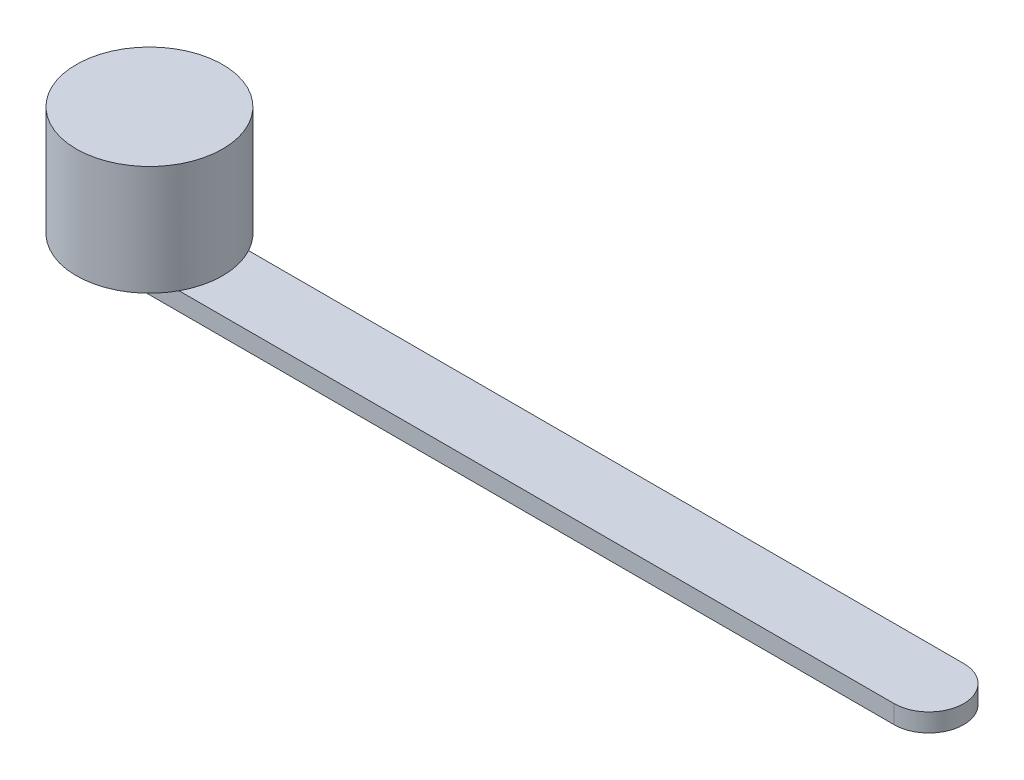
SolidWorks part; units mm, degrees
ref_plane "Front Plane" through (0, 0, 0) normal (0, 0, 1) x (1, 0, 0)
ref_plane "Top Plane" through (0, 0, 0) normal (0, 1, 0) x (1, 0, 0)
ref_plane "Right Plane" through (0, 0, 0) normal (1, 0, 0) x (0, 0, -1)
sketch "Sketch1" plane through (0, 0, 0) normal (0, 1, 0) x (1, 0, 0)
  line L0 (-18.2955, 0) -> (93.7045, 0) construction
  line L1 (-18.2955, 4.75) -> (93.7045, 4.75)
  line L2 (-18.2955, -4.75) -> (93.7045, -4.75)
  arc A0 (-18.2955, 4.75) -> (-18.2955, -4.75) centre (-18.2955, 0) ccw
  arc A1 (93.7045, -4.75) -> (93.7045, 4.75) centre (93.7045, 0) ccw
  point P3 (37.7045, 0)
  dimension "D1" = 9.5
  dimension "D2" = 112
extrude "Boss-Extrude1" add sketch "Sketch1" along normal blind 2.5 contours L1 A1 L2 A0
sketch "Sketch2" plane through (0, 2.5, 0) normal (0, 1, 0) x (1, 0, 0)
  circle A0 centre (-12.7955, 0) radius 10
  arc A1 (-18.2955, 4.75) -> (-18.2955, -4.75) centre (-18.2955, 0) ccw construction
  dimension "D1" = 5.5
  dimension "D2" = 20
extrude "Boss-Extrude2" add sketch "Sketch2" along normal blind 15
sketch "Sketch3" plane through (0, 17.5, 0) normal (0, 1, 0) x (1, 0, 0)
  circle A0 centre (-12.7955, 0) radius 7.5
extrude "Cut-Extrude1" cut sketch "Sketch3" against normal blind 2.5 and the other way through all
sketch "Sketch4" plane through (0, 15, 0) normal (0, 1, 0) x (1, 0, 0)
  circle A0 centre (-12.7955, 0) radius 7.5
extrude "Boss-Extrude3" add sketch "Sketch4" along normal blind 2.5
